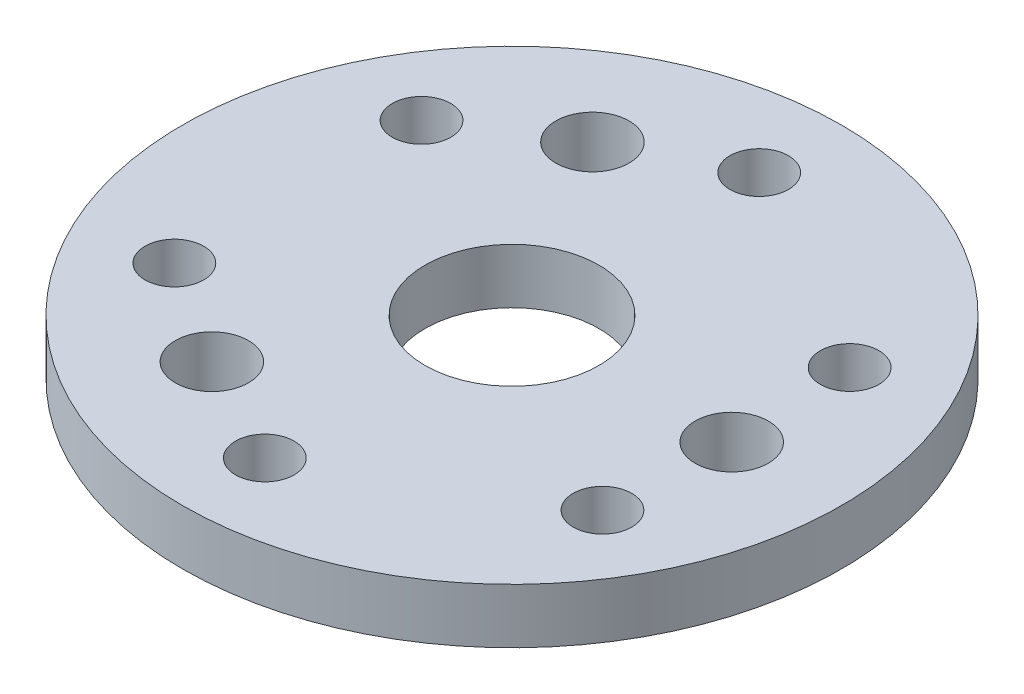
SolidWorks part; units mm, degrees
ref_plane "前视基准面" through (0, 0, 0) normal (0, 0, 1) x (1, 0, 0)
ref_plane "上视基准面" through (0, 0, 0) normal (0, 1, 0) x (1, 0, 0)
ref_plane "右视基准面" through (0, 0, 0) normal (1, 0, 0) x (0, 0, -1)
other "Configuration Table"
sketch "草图1" plane through (0, 0, 0) normal (0, 1, 0) x (1, 0, 0)
  circle A0 centre (0, 0) radius 18
  circle A1 centre (0, 0) radius 13.5 construction
  circle A2 centre (0, 13.5) radius 1.6
  circle A3 centre (11.6913, 6.75) radius 1.6
  circle A4 centre (11.6913, -6.75) radius 1.6
  circle A5 centre (0, -13.5) radius 1.6
  circle A6 centre (-11.6913, -6.75) radius 1.6
  circle A7 centre (-11.6913, 6.75) radius 1.6
  circle A8 centre (0, 0) radius 12 construction
  circle A9 centre (12, 0) radius 2
  circle A10 centre (-6, -10.3923) radius 2
  circle A11 centre (-6, 10.3923) radius 2
  dimension "D1" = 36
  dimension "D2" = 27
  dimension "D3" = 3.2
  dimension "D5" = 24
  dimension "D6" = 4
  dimension "D4" = 6
  dimension "D7" = 3
extrude "凸台-拉伸1" add sketch "草图1" along normal blind 3
sketch "草图3" plane through (0, 3, 0) normal (0, 1, 0) x (1, 0, 0)
  circle A0 centre (0, 0) radius 4.75
  dimension "D1" = 9.5
extrude "切除-拉伸1" cut sketch "草图3" against normal blind 4
